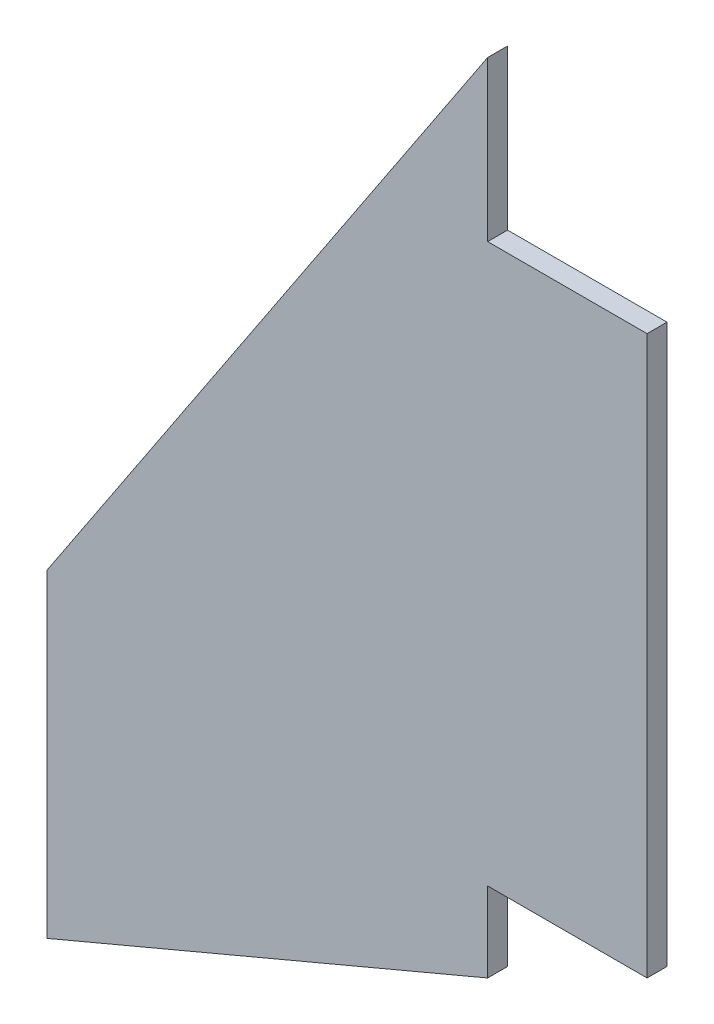
SolidWorks part; units mm, degrees
ref_plane "Front Plane" through (0, 0, 0) normal (0, 0, 1) x (1, 0, 0)
ref_plane "Top Plane" through (0, 0, 0) normal (0, 1, 0) x (1, 0, 0)
ref_plane "Right Plane" through (0, 0, 0) normal (1, 0, 0) x (0, 0, -1)
sketch "Sketch1" plane through (0, 0, 0) normal (0, 0, 1) x (1, 0, 0)
  line L0 (0, 0) -> (0, 88.9)
  line L1 (0, 88.9) -> (-25.4, 88.9)
  line L2 (-25.4, 88.9) -> (-25.4, 114.3)
  line L3 (-25.4, 114.3) -> (-95.6019, 8.4667)
  line L4 (-95.6019, 8.4667) -> (-95.6019, -42.3333)
  line L5 (-95.6019, -42.3333) -> (-25.4, -12.7)
  line L6 (-25.4, -12.7) -> (-25.4, 0)
  line L7 (-25.4, 0) -> (0, 0)
  point P3 (-90.6309, 5.3324)
  dimension "D1" = 88.9
  dimension "D2" = 25.4
  dimension "D3" = 12.7
  dimension "D4" = 25.4
  dimension "D5" = 50.8
  dimension "D6" = 127
  dimension "D7" = 76.2
extrude "Boss-Extrude1" add sketch "Sketch1" along normal mid plane 3.175
